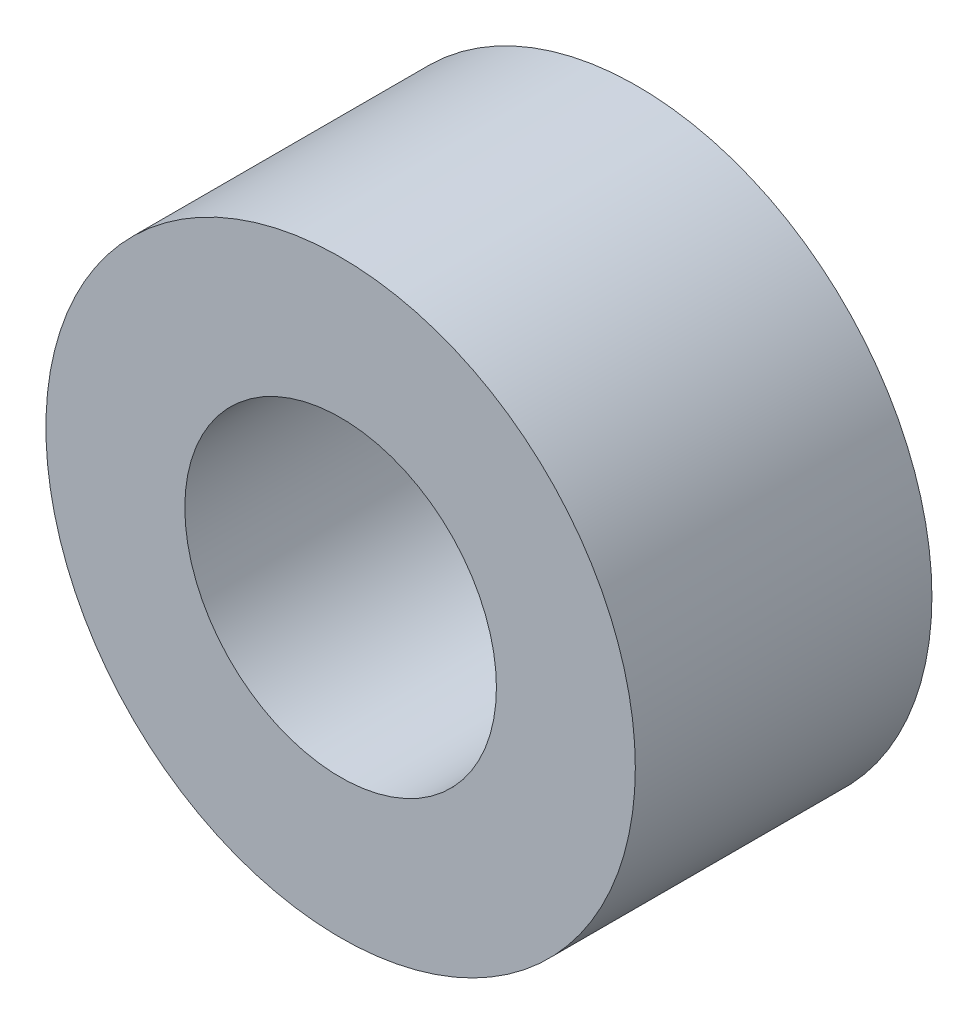
SolidWorks part; units mm, degrees
ref_plane "Front Plane" through (0, 0, 0) normal (0, 0, 1) x (1, 0, 0)
ref_plane "Top Plane" through (0, 0, 0) normal (0, 1, 0) x (1, 0, 0)
ref_plane "Right Plane" through (0, 0, 0) normal (1, 0, 0) x (0, 0, -1)
sketch "Sketch1" plane through (0, 0, 0) normal (0, 0, 1) x (1, 0, 0)
  circle A0 centre (0, 0) radius 7.85
  circle A1 centre (0, 0) radius 4.15
  dimension "D1" = 15.7
  dimension "D2" = 8.3
extrude "Boss-Extrude1" add sketch "Sketch1" along normal blind 7.9
